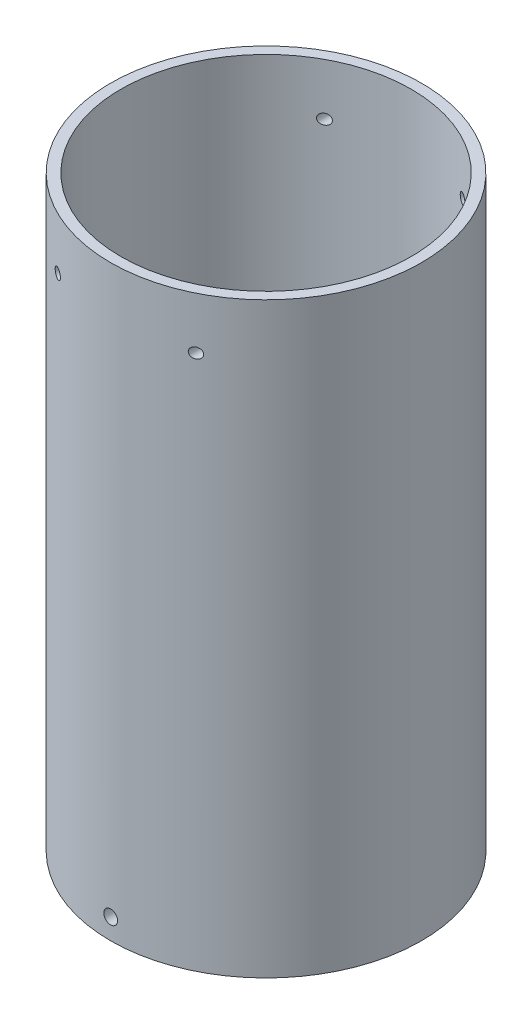
SolidWorks part; units mm, degrees
material "Aluminium"
ref_plane "Front Plane" through (0, 0, 0) normal (0, 0, 1) x (1, 0, 0)
ref_plane "Top Plane" through (0, 0, 0) normal (0, 1, 0) x (1, 0, 0)
ref_plane "Right Plane" through (0, 0, 0) normal (1, 0, 0) x (0, 0, -1)
sketch "Sketch1" plane through (0, 0, 0) normal (0, 1, 0) x (1, 0, 0)
  circle A0 centre (0, 0) radius 45
  circle A1 centre (0, 0) radius 42
  dimension "D1" = 3
  dimension "D2" = 90
extrude "Boss-Extrude1" add sketch "Sketch1" against normal blind 170
sketch "Sketch2" plane through (0, 0, 0) normal (0, 0, 1) x (1, 0, 0)
  line L0 (-45, -170) -> (45, -170) construction
  line L1 (0, -164) -> (0, -170) construction
  line L2 (20, -15) -> (-20, -15) construction
  line L3 (0, 0) -> (0, -15) construction
  line L4 (42, 0) -> (-42, 0) construction
  circle A0 centre (0, -164) radius 2
  circle A1 centre (-20, -15) radius 1.5
  circle A2 centre (20, -15) radius 1.5
  dimension "D1" = 4
  dimension "D2" = 6
  dimension "D5" = 3
  dimension "D3" = 15
  dimension "D4" = 40
extrude "Cut-Extrude1" cut sketch "Sketch2" against normal through all both and the other way through all
